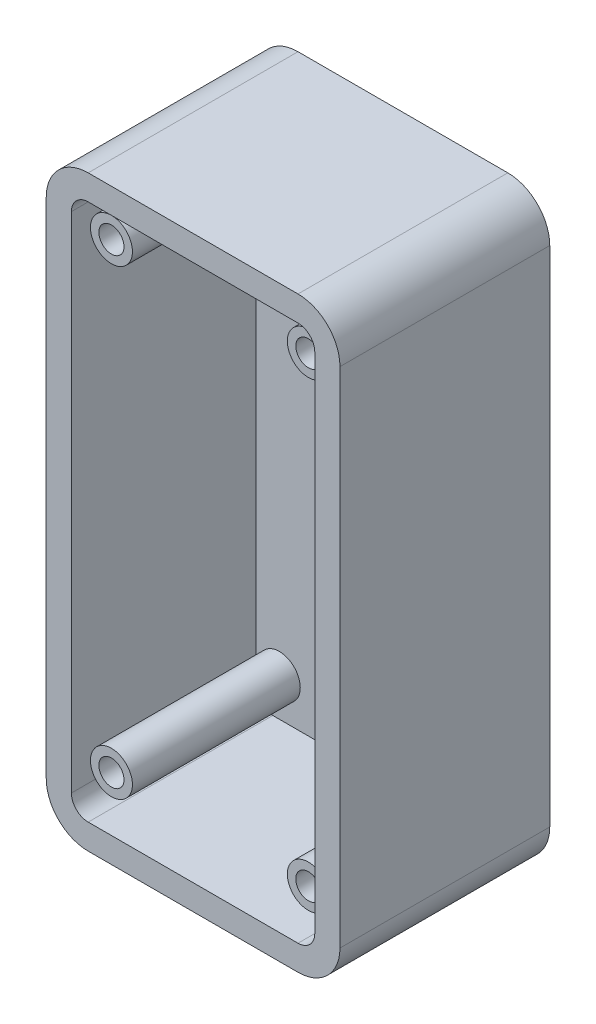
SolidWorks part; units mm, degrees
ref_plane "前视基准面" through (0, 0, 0) normal (0, 0, 1) x (1, 0, 0)
ref_plane "上视基准面" through (0, 0, 0) normal (0, 1, 0) x (1, 0, 0)
ref_plane "右视基准面" through (0, 0, 0) normal (1, 0, 0) x (0, 0, -1)
sketch "草图1" plane through (0, 0, 0) normal (0, 0, 1) x (1, 0, 0)
  line L1 (-193.4252, 70) -> (-168.4252, 70)
  line L2 (-198.4252, 65) -> (-198.4252, 5)
  line L3 (-193.4252, 0) -> (-168.4252, 0)
  line L4 (-163.4252, 65) -> (-163.4252, 5)
  line L5 (-198.4252, 70) -> (-163.4252, 0) construction
  line L6 (-198.4252, 0) -> (-163.4252, 70) construction
  arc A0 (-198.4252, 5) -> (-193.4252, 0) centre (-193.4252, 5) ccw
  arc A1 (-168.4252, 0) -> (-163.4252, 5) centre (-168.4252, 5) ccw
  arc A2 (-168.4252, 70) -> (-163.4252, 65) centre (-168.4252, 65) cw
  arc A3 (-193.4252, 70) -> (-198.4252, 65) centre (-193.4252, 65) ccw
  point P0 (-180.9252, 35)
  dimension "D3" = 5
  dimension "D1" = 70
  dimension "D2" = 35
extrude "凸台-拉伸1" add sketch "草图1" along normal blind 25
shell "抽壳2" thickness 3
sketch "草图3" plane through (0, 0, 3) normal (0, 0, 1) x (1, 0, 0)
  line L0 (-124.8248, 35) -> (-208.0256, 35) construction
  line L1 (-180.9252, 64.1908) -> (-180.9252, 32.4467) construction
  circle A0 centre (-192.6567, 62.5) radius 2.5
  circle A1 centre (-192.6567, 7.5) radius 2.5
  circle A2 centre (-169.1937, 62.5) radius 2.5
  circle A3 centre (-169.1937, 7.5) radius 2.5
  point P13 (-166.4252, 35)
  point P14 (-166.4252, 35)
  dimension "D1" = 5
  dimension "D2" = 55
extrude "凸台-拉伸4" add sketch "草图3" along normal blind 20
sketch "草图4" plane through (0, 0, 3) normal (0, 0, 1) x (1, 0, 0)
  circle A0 centre (-192.6567, 62.5) radius 1.5
  circle A1 centre (-169.1937, 62.5) radius 1.5
  circle A2 centre (-169.1937, 7.5) radius 1.5
  circle A3 centre (-192.6567, 7.5) radius 1.5
  dimension "D1" = 3
extrude "切除-拉伸4" cut sketch "草图4" against normal through all and the other way through all
